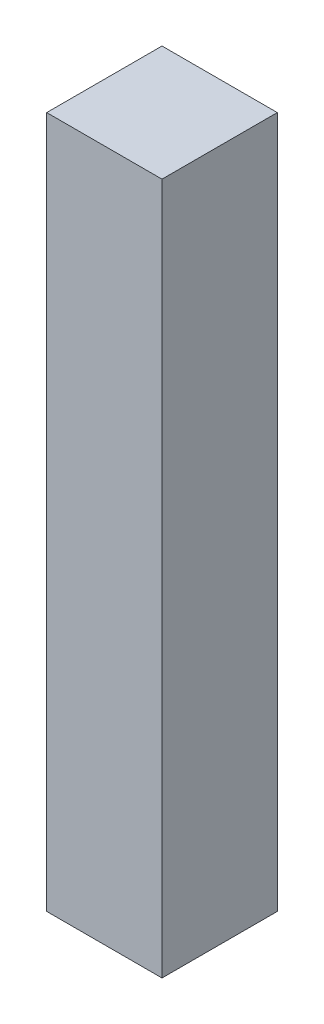
SolidWorks part; units mm, degrees
ref_plane "Front" through (0, 0, 0) normal (0, 0, 1) x (1, 0, 0)
ref_plane "Top" through (0, 0, 0) normal (0, 1, 0) x (1, 0, 0)
ref_plane "Right" through (0, 0, 0) normal (1, 0, 0) x (0, 0, -1)
sketch "Sketch1" plane through (0, 0, 0) normal (0, 1, 0) x (1, 0, 0)
  line L1 (0, 0) -> (5, 0)
  line L2 (0, 0) -> (0, 5)
  line L3 (0, 5) -> (5, 5)
  line L4 (5, 0) -> (5, 5)
  dimension "D1" = 5
  dimension "D2" = 5
extrude "Boss-Extrude1" add sketch "Sketch1" along normal blind 30 contours L2 L3 L4 L1
